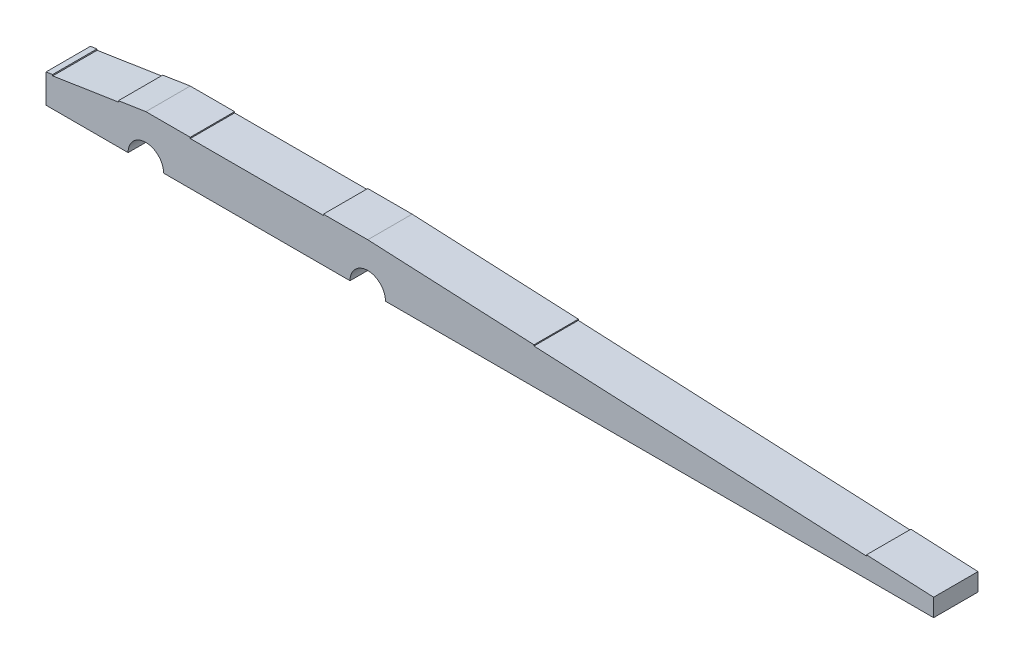
SolidWorks part; units mm, degrees
material "Balsa"
ref_plane "Plan de face" through (0, 0, 0) normal (0, 0, 1) x (1, 0, 0)
ref_plane "Plan de dessus" through (0, 0, 0) normal (0, 1, 0) x (1, 0, 0)
ref_plane "Plan de droite" through (0, 0, 0) normal (1, 0, 0) x (0, 0, -1)
sketch "Sketch1" plane through (0, 0, 0) normal (0, 0, 1) x (1, 0, 0)
  line L0 (-8, 0) -> (-92, 0)
  line L1 (8, 0) -> (255, 0)
  line L2 (-108, 0) -> (-145, 0)
  line L3 (-100, 20) -> (0, 20)
  line L4 (0, 20) -> (255, 8)
  line L6 (-100, 20) -> (-145, 13)
  line L7 (-145, 0) -> (-145, 13)
  line L15 (-100, 0) -> (-100, 48.6354) construction
  line L16 (0, 0) -> (0, 46.3997) construction
  line L17 (255, 8) -> (255, 0)
  arc A0 (8, 0) -> (-8, 0) centre (0, 0) ccw
  arc A1 (-92, 0) -> (-108, 0) centre (-100, 0) ccw
  dimension "D6" = 8
  dimension "D11" = 8
  dimension "D1" = 100
  dimension "D2" = 45
  dimension "D3" = 400
  dimension "D4" = 8
  dimension "D5" = 20
  dimension "D9" = 7
extrude "Boss-Extrude1" add sketch "Sketch1" along normal blind 20
sketch "Sketch2" plane through (0.9391, 19.9558, 0) normal (0.047, 0.9989, 0) x (0.9989, -0.047, 0)
  line L0 (254.3421, 0) -> (-0.9401, 0) construction
  line L1 (74.0599, 0) -> (224.0599, 0)
  line L2 (74.0599, 0) -> (74.0599, -20)
  line L3 (74.0599, -20) -> (224.0599, -20)
  line L4 (224.0599, 0) -> (224.0599, -20)
  line L5 (254.3421, -20) -> (-0.9401, -20) construction
  line L6 (-0.9401, -20) -> (-0.9401, 0) construction
  dimension "D1" = 150
  dimension "D2" = 75
extrude "RopeGroove1" cut sketch "Sketch2" against normal blind 0.5
sketch "Sketch4" plane through (0, 20, 0) normal (0, 1, 0) x (1, 0, 0)
  line L0 (0, 0) -> (-100, 0) construction
  line L1 (-80, 0) -> (-20, 0)
  line L2 (-80, 0) -> (-80, -20)
  line L3 (-80, -20) -> (-20, -20)
  line L4 (-20, 0) -> (-20, -20)
  line L5 (0, -20) -> (-100, -20) construction
  line L6 (-50, -20) -> (-50, 0) construction
  point P10 (-50, -20)
  dimension "D1" = 60
extrude "RopeGroove2" cut sketch "Sketch4" against normal blind 0.5
sketch "Sketch5" plane through (-5.4002, 34.7155, 0) normal (-0.1537, 0.9881, 0) x (0.9881, 0.1537, 0)
  line L0 (-95.7375, 0) -> (-141.2787, 0) construction
  line L1 (-138.2787, 0) -> (-108.2787, 0)
  line L2 (-138.2787, 0) -> (-138.2787, -20)
  line L3 (-138.2787, -20) -> (-108.2787, -20)
  line L4 (-108.2787, 0) -> (-108.2787, -20)
  line L5 (-95.7375, -20) -> (-141.2787, -20) construction
  line L7 (-141.2787, -20) -> (-141.2787, 0) construction
  dimension "D1" = 30
  dimension "D2" = 3
extrude "RopeGroove3" cut sketch "Sketch5" against normal blind 0.5
